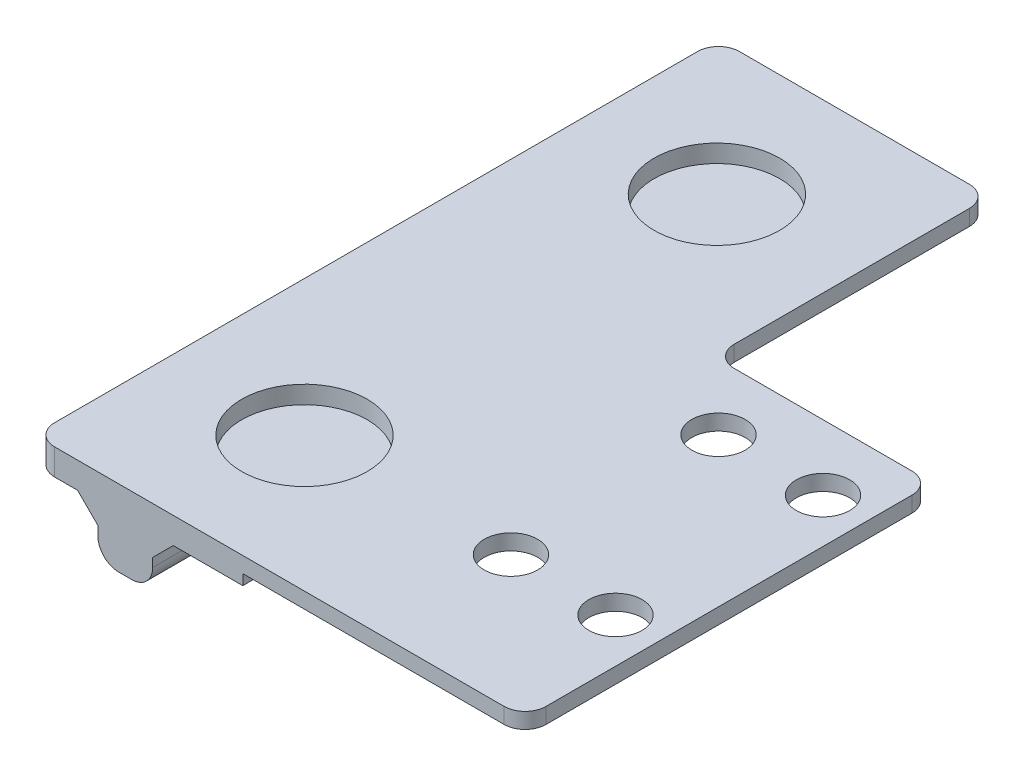
SolidWorks part; units mm, degrees
ref_plane "Front Plane" through (0, 0, 0) normal (0, 0, 1) x (1, 0, 0)
ref_plane "Top Plane" through (0, 0, 0) normal (0, 1, 0) x (1, 0, 0)
ref_plane "Right Plane" through (0, 0, 0) normal (1, 0, 0) x (0, 0, -1)
sketch "Sketch1" plane through (0, 0, 0) normal (0, 0, 1) x (1, 0, 0)
  line L0 (-10, -1.25) -> (-5.8, -1.25) construction
  line L1 (-10, -1.25) -> (-5.8, -1.25)
  line L2 (-10, -1.25) -> (-10, 1.25)
  line L3 (-10, 1.25) -> (10, 1.25)
  line L4 (10, -1.25) -> (10, -0.25)
  line L5 (-10, -1.25) -> (10, 1.25) construction
  line L6 (-10, 1.25) -> (10, -1.25) construction
  line L7 (10, 1.25) -> (16, 1.25)
  line L9 (10, -0.25) -> (16, -0.25)
  line L10 (16, 1.25) -> (16, -0.25)
  line L11 (-5.8, -1.25) -> (-3.8613, -3.1887)
  line L12 (3.35, -1.25) -> (9.1, -1.25) construction
  line L13 (-5.8, -2.1458) -> (3.35, -2.1458) construction
  line L14 (3.35, -1.25) -> (1.3804, -3.2196)
  line L16 (3.35, -1.25) -> (10, -1.25)
  line L18 (-3.8613, -3.1887) -> (-3.8613, -6.0585)
  line L19 (-3.8613, -6.0585) -> (1.3804, -6.0585)
  line L20 (1.3804, -6.0585) -> (1.3804, -3.2196)
  point P0 (0, 0)
extrude "Boss-Extrude1" add sketch "Sketch1" along normal blind 65.5
sketch "Sketch2" plane through (0, 0, 0) normal (0, 1, 0) x (1, 0, 0)
  line L0 (-10, -12.9) -> (2.75, -12.9) construction
  line L1 (-10, -65.5) -> (-10, 0) construction
  line L2 (-1.2344, 0) -> (-1.2344, -12.9) construction
  line L4 (3, -65.5) -> (3, -52.6) construction
  line L5 (16, -65.5) -> (-10, -65.5) construction
  circle A2 centre (2.75, -12.9) radius 6
  circle A3 centre (3, -52.6) radius 6
extrude "Cut-Extrude1" cut sketch "Sketch2" against normal blind 1.7 from surface at 1.25 starting at face at (3, 1.25, 32.75)
sketch "Sketch3" plane through (0, 0, 0) normal (0, 1, 0) x (1, 0, 0)
  line L0 (3, -52.6) -> (16, -52.6) construction
  line L1 (16, -65.5) -> (16, 0) construction
  line L2 (16, -52.6) -> (16, -65.5) construction
  line L3 (16, -65.5) -> (37, -65.5) construction
  line L4 (16, -65.5) -> (37, -65.5)
  line L5 (16, -65.5) -> (16, -26.5)
  line L6 (16, -26.5) -> (37, -26.5)
  line L7 (37, -65.5) -> (37, -26.5)
  line L9 (37, -62.6498) -> (32.75, -62.6498) construction
  line L10 (32.75, -65.5) -> (32.75, -52.6) construction
  line L11 (32.75, -52.6) -> (32.75, -32.75) construction
  line L12 (32.75, -52.6) -> (22.75, -52.6) construction
  line L13 (32.75, -32.75) -> (22.75, -32.75) construction
  circle A0 centre (32.75, -52.6) radius 2.55
  circle A1 centre (32.75, -32.75) radius 2.55
  circle A2 centre (22.75, -52.6) radius 2.55
  circle A3 centre (22.75, -32.75) radius 2.55
extrude "Boss-Extrude2" add sketch "Sketch3" along normal up to surface and the other way up to surface up to face at (2.75, 1.25, 6.9) other way up to face at (13, -0.25, 32.75)
fillet "Fillet1" radius 2 8 edges at (-3.8613, -6.0585, 32.75) (1.3804, -6.0585, 32.75) (16, 0.5, 0) (-10, 0, 0) (-10, 0, 65.5) (37, 0.5, 26.5) (37, 0.5, 65.5) (16, 0.5, 26.5)
